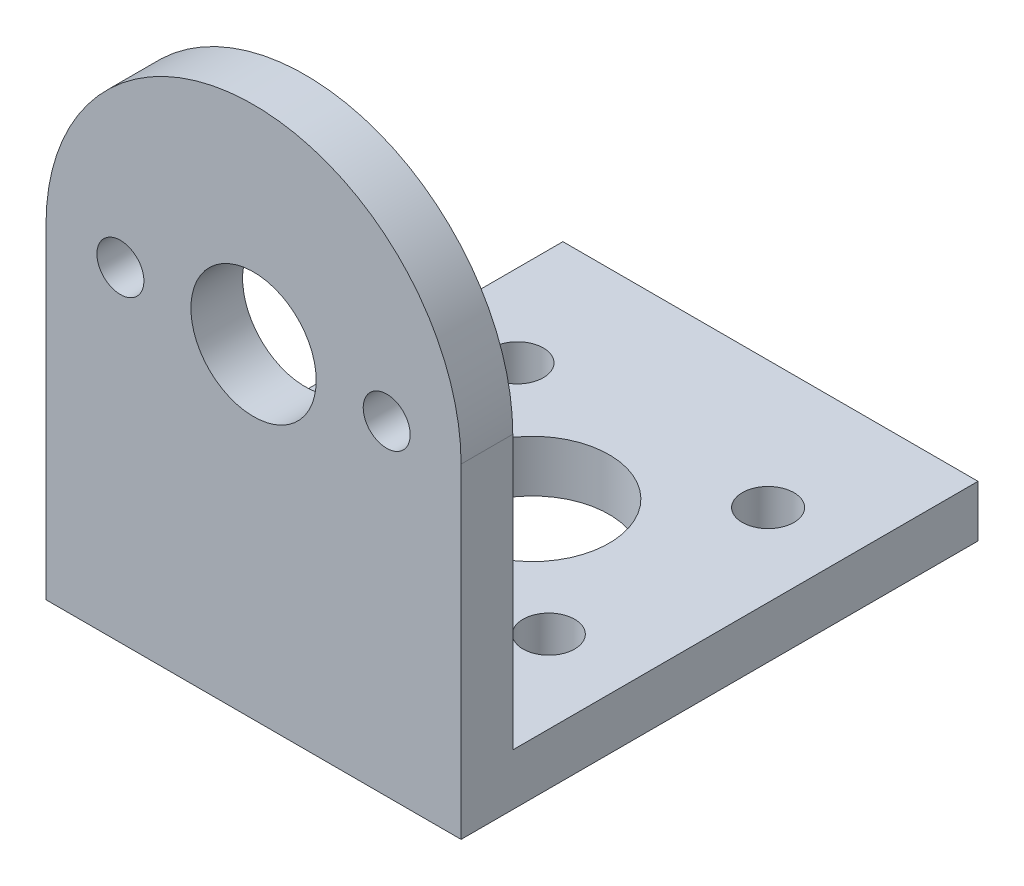
SolidWorks part; units mm, degrees
ref_plane "前视基准面" through (0, 0, 0) normal (0, 0, 1) x (1, 0, 0)
ref_plane "上视基准面" through (0, 0, 0) normal (0, 1, 0) x (1, 0, 0)
ref_plane "右视基准面" through (0, 0, 0) normal (1, 0, 0) x (0, 0, -1)
sketch "草图1" plane through (0, 0, 0) normal (0, 0, 1) x (1, 0, 0)
  line L0 (0, -55) -> (0, 55) construction
  line L2 (-13.25, 0) -> (-13.25, -20.75)
  line L3 (-13.25, -20.75) -> (13.25, -20.75)
  line L4 (13.25, 0) -> (13.25, -20.75)
  arc A1 (-13.25, 0) -> (13.25, 0) centre (0, 0) cw
  circle A2 centre (0, 0) radius 4
  circle A3 centre (-8.5, 0) radius 1.5
  circle A4 centre (8.5, 0) radius 1.5
  dimension "D1" = 26.5
  dimension "D3" = 8
  dimension "D4" = 3
  dimension "D5" = 8.5
  dimension "D6" = 13.25
  dimension "D2" = 20.75
extrude "凸台-拉伸1" add sketch "草图1" along normal blind 3.3
sketch "草图2" plane through (0, 0, 0) normal (0, 0, 1) x (1, 0, 0)
  line L0 (-13.25, 0) -> (-13.25, -20.75) construction
  line L1 (13.25, -20.75) -> (-13.25, -20.75)
  line L2 (13.25, -20.75) -> (13.25, -17.45)
  line L3 (13.25, -17.45) -> (-13.25, -17.45)
  line L4 (-13.25, -20.75) -> (-13.25, -17.45)
  dimension "D1" = 3.3
extrude "凸台-拉伸2" add sketch "草图2" against normal blind 29.7
sketch "草图3" plane through (0, -17.45, 0) normal (0, 1, 0) x (1, 0, 0)
  line L0 (13.25, 29.7) -> (-13.25, 29.7) construction
  line L1 (-13.25, 29.7) -> (-13.25, 0) construction
  line L3 (0, -18.15) -> (0, 18.15) construction
  circle A0 centre (0, 14.5) radius 4.9
  circle A1 centre (-8, 21.55) radius 1.65
  circle A2 centre (-8, 7.55) radius 1.65
  circle A3 centre (8, 7.55) radius 1.65
  circle A4 centre (8, 21.55) radius 1.65
  dimension "D1" = 9.8
  dimension "D2" = 15.2
  dimension "D3" = 8.15
  dimension "D4" = 3.3
  dimension "D6" = 3.3
  dimension "D7" = 14
  dimension "D8" = 5.25
  dimension "D5" = 5.25
extrude "切除-拉伸1" cut sketch "草图3" against normal up to surface (3.3 mm away) up to face at (0, -20.75, -13.2)
